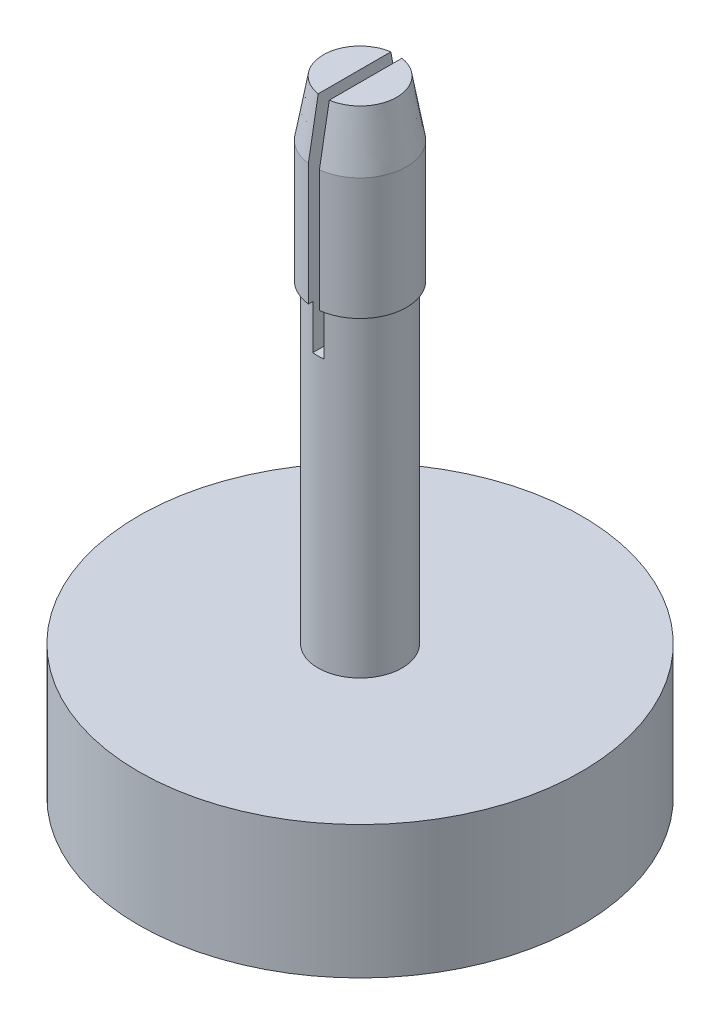
SolidWorks part; units mm, degrees
ref_plane "Plan de face" through (0, 0, 0) normal (0, 0, 1) x (1, 0, 0)
ref_plane "Plan de dessus" through (0, 0, 0) normal (0, 1, 0) x (1, 0, 0)
ref_plane "Plan de droite" through (0, 0, 0) normal (1, 0, 0) x (0, 0, -1)
sketch "Esquisse2" plane through (0, 0, 0) normal (0, 1, 0) x (1, 0, 0)
  circle A0 centre (0, 0) radius 5
extrude "Boss.-Extru.1" add sketch "Esquisse2" along normal blind 3
sketch "Esquisse3" plane through (0, 3, 0) normal (0, 1, 0) x (1, 0, 0)
  circle A0 centre (0, 0) radius 0.95
  dimension "D1" = 1.9
extrude "Boss.-Extru.2" add sketch "Esquisse3" along normal blind 7.1
ref_plane "Plan1" through (0, 10.1, 0) normal (0, 1, 0) x (1, 0, 0)
sketch "Esquisse4" plane through (0, 10.1, 0) normal (0, 1, 0) x (1, 0, 0)
  circle A0 centre (0, 0) radius 1.05
  dimension "D1" = 2.1
extrude "Boss.-Extru.3" add sketch "Esquisse4" along normal blind 4
chamfer "Chanfrein3" distance 1.25 angle 10 1 edges at (0, 14.1, 1.05)
ref_plane "Plan2" through (0, 14.1, 0) normal (0, 1, 0) x (1, 0, 0)
sketch "Esquisse5" plane through (0, 14.1, 0) normal (0, 1, 0) x (1, 0, 0)
  line L1 (0.125, 1.5) -> (-0.125, 1.5)
  line L2 (0.125, 1.5) -> (0.125, -1.5)
  line L3 (0.125, -1.5) -> (-0.125, -1.5)
  line L4 (-0.125, 1.5) -> (-0.125, -1.5)
  line L5 (0.125, 1.5) -> (-0.125, -1.5) construction
  line L6 (0.125, -1.5) -> (-0.125, 1.5) construction
  point P0 (0, 0)
  dimension "D1" = 0.25
  dimension "D2" = 3
extrude "Enlèv. mat.-Extru.1" cut sketch "Esquisse5" against normal blind 5
